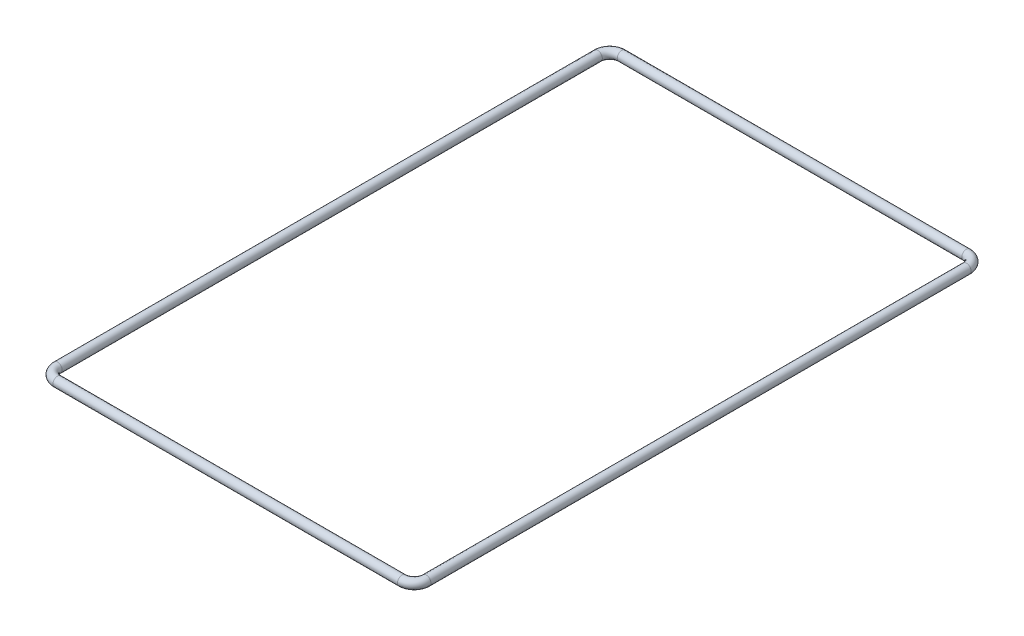
SolidWorks part; units mm, degrees
ref_plane "Front Plane" through (0, 0, 0) normal (0, 0, 1) x (1, 0, 0)
ref_plane "Top Plane" through (0, 0, 0) normal (0, 1, 0) x (1, 0, 0)
ref_plane "Right Plane" through (0, 0, 0) normal (1, 0, 0) x (0, 0, -1)
sketch "Sketch1" plane through (0, 0, 0) normal (0, 1, 0) x (1, 0, 0)
  line L0 (-96.133, -144.4301) -> (88.867, -144.4301) construction
  line L1 (-101.133, -139.4301) -> (-101.133, 150.5699) construction
  line L2 (-96.133, 155.5699) -> (88.867, 155.5699) construction
  line L3 (93.867, -139.4301) -> (93.867, 150.5699) construction
  line L4 (-96.133, 157.0699) -> (88.867, 157.0699)
  line L5 (95.367, -139.4301) -> (95.367, 150.5699)
  line L6 (-96.133, -145.9301) -> (88.867, -145.9301)
  line L7 (-102.633, -139.4301) -> (-102.633, 150.5699)
  arc A0 (88.867, -144.4301) -> (93.867, -139.4301) centre (88.867, -139.4301) ccw construction
  arc A1 (93.867, 150.5699) -> (88.867, 155.5699) centre (88.867, 150.5699) ccw construction
  arc A2 (-96.133, 155.5699) -> (-101.133, 150.5699) centre (-96.133, 150.5699) ccw construction
  arc A3 (-101.133, -139.4301) -> (-96.133, -144.4301) centre (-96.133, -139.4301) ccw construction
  arc A4 (95.367, 150.5699) -> (88.867, 157.0699) centre (88.867, 150.5699) ccw
  arc A5 (88.867, -145.9301) -> (95.367, -139.4301) centre (88.867, -139.4301) ccw
  arc A6 (-102.633, -139.4301) -> (-96.133, -145.9301) centre (-96.133, -139.4301) ccw
  arc A7 (-96.133, 157.0699) -> (-102.633, 150.5699) centre (-96.133, 150.5699) ccw
  dimension "D1" = 1.5
sweep "Sweep1" add path "Sketch1" circular profile diameter 5 parameters "D3"=5
